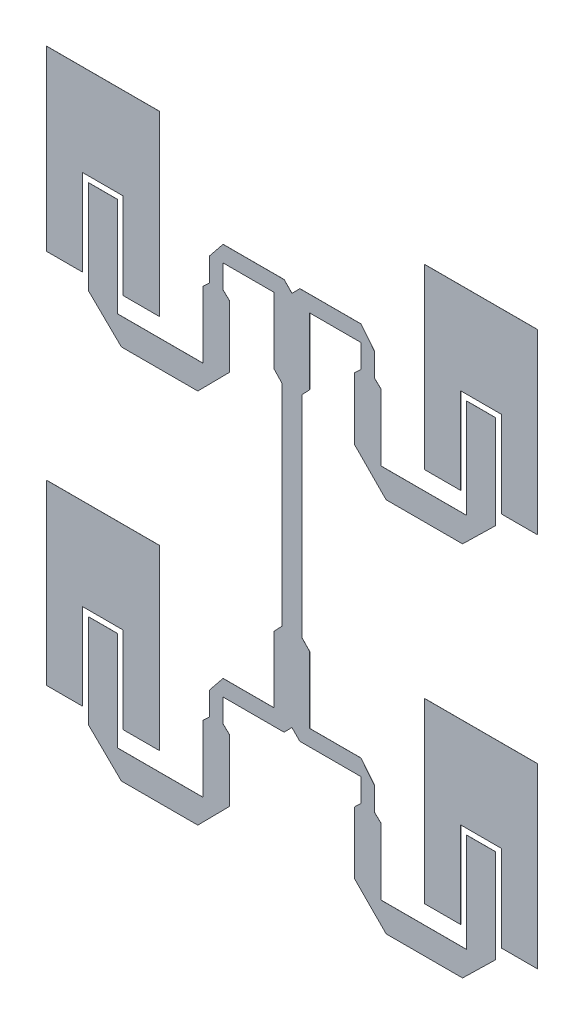
SolidWorks part; units mm, degrees
material "Медь"
ref_plane "Спереди" through (0, 0, 0) normal (0, 0, 1) x (1, 0, 0)
ref_plane "Сверху" through (0, 0, 0) normal (0, 1, 0) x (1, 0, 0)
ref_plane "Справа" through (0, 0, 0) normal (1, 0, 0) x (0, 0, -1)
sketch "Patch1" plane through (0, 0, 0) normal (0, 0, 1) x (1, 0, 0)
  line L0 (0, 0) -> (0, 64.0927) construction
  line L1 (-56.8537, 64.0927) -> (-30.6917, 64.0927)
  line L2 (-56.8537, 64.0927) -> (-56.8537, 22.9447)
  line L3 (-56.8537, 22.9447) -> (-48.4717, 22.9447)
  line L4 (-30.6917, 64.0927) -> (-30.6917, 22.9447)
  line L5 (-56.8537, 64.0927) -> (-30.6917, 22.9447) construction
  line L6 (-56.8537, 22.9447) -> (-30.6917, 64.0927) construction
  line L7 (-43.7727, 43.5187) -> (-43.7727, 22.9447) construction
  line L8 (43.7727, 43.5187) -> (43.7727, 22.9447) construction
  line L9 (-48.4717, 22.9447) -> (-48.4717, 42.926)
  line L10 (-48.4717, 42.926) -> (-39.0737, 42.926)
  line L11 (-39.0737, 22.9447) -> (-39.0737, 42.926)
  line L12 (-39.0737, 22.9447) -> (-30.6917, 22.9447)
  line L13 (56.8537, 22.9447) -> (30.6917, 64.0927) construction
  line L14 (56.8537, 64.0927) -> (30.6917, 22.9447) construction
  line L15 (39.0737, 22.9447) -> (30.6917, 22.9447)
  line L16 (39.0737, 22.9447) -> (39.0737, 42.926)
  line L17 (48.4717, 42.926) -> (39.0737, 42.926)
  line L18 (48.4717, 22.9447) -> (48.4717, 42.926)
  line L19 (30.6917, 64.0927) -> (30.6917, 22.9447)
  line L20 (56.8537, 22.9447) -> (48.4717, 22.9447)
  line L21 (56.8537, 64.0927) -> (56.8537, 22.9447)
  line L22 (56.8537, 64.0927) -> (30.6917, 64.0927)
  line L23 (-39.0737, -64.0927) -> (-30.6917, -64.0927)
  line L24 (-30.6917, -22.9447) -> (-30.6917, -64.0927)
  line L25 (-56.8537, -22.9447) -> (-30.6917, -22.9447)
  line L26 (-56.8537, -22.9447) -> (-30.6917, -64.0927) construction
  line L27 (-48.4717, -44.1113) -> (-39.0737, -44.1113)
  line L28 (-56.8537, -22.9447) -> (-56.8537, -64.0927)
  line L29 (-48.4717, -64.0927) -> (-48.4717, -44.1113)
  line L30 (-56.8537, -64.0927) -> (-30.6917, -22.9447) construction
  line L31 (-39.0737, -64.0927) -> (-39.0737, -44.1113)
  line L32 (-56.8537, -64.0927) -> (-48.4717, -64.0927)
  line L33 (-43.7727, -43.5187) -> (-43.7727, -64.0927) construction
  line L34 (43.7727, -43.5187) -> (43.7727, -64.0927) construction
  line L35 (56.8537, -64.0927) -> (30.6917, -22.9447) construction
  line L36 (56.8537, -22.9447) -> (30.6917, -64.0927) construction
  line L37 (56.8537, -64.0927) -> (48.4717, -64.0927)
  line L38 (39.0737, -64.0927) -> (39.0737, -44.1113)
  line L39 (48.4717, -64.0927) -> (48.4717, -44.1113)
  line L40 (56.8537, -22.9447) -> (56.8537, -64.0927)
  line L41 (48.4717, -44.1113) -> (39.0737, -44.1113)
  line L42 (56.8537, -22.9447) -> (30.6917, -22.9447)
  line L43 (30.6917, -22.9447) -> (30.6917, -64.0927)
  line L44 (39.0737, -64.0927) -> (30.6917, -64.0927)
  point P0 (-43.7727, 43.5187)
  point P24 (-43.7727, -43.5187)
  dimension "D1" = 41.148
  dimension "D2" = 26.162
  dimension "D3" = 43.7727
  dimension "D5" = 19.9813
  dimension "D6" = 8.382
  dimension "D4" = 43.5187
  dimension "D7" = 41.148
  dimension "D8" = 26.162
  dimension "D9" = 19.9813
  dimension "D10" = 8.382
  dimension "D11" = 43.7727
  dimension "D12" = 43.5187
sketch "Feed1" plane through (0, 0, 0) normal (0, 0, 1) x (1, 0, 0)
  line L0 (-48.4717, 42.926) -> (-39.0737, 42.926) construction
  line L1 (-47.117, 41.5713) -> (-40.4283, 41.5713)
  line L2 (-47.117, 41.5713) -> (-47.117, 19.8967)
  line L3 (-47.117, 19.8967) -> (-39.497, 12.446)
  line L4 (-40.4283, 41.5713) -> (-40.4283, 18.6267)
  line L5 (-48.4717, 22.9447) -> (-48.4717, 42.926) construction
  line L6 (-14.4357, 19.8967) -> (-21.8017, 12.446)
  line L7 (-20.6163, 34.036) -> (-19.0923, 35.4753)
  line L8 (14.4357, -67.1407) -> (14.4357, -52.832)
  line L9 (-39.497, 12.446) -> (-21.8017, 12.446)
  line L10 (-20.6163, 18.6267) -> (-20.6163, 34.036)
  line L11 (1.8203, 44.7887) -> (0, 42.926)
  line L12 (40.4283, -68.4107) -> (20.6163, -68.4107)
  line L13 (-19.0923, 40.894) -> (-19.0923, 35.4753)
  line L14 (39.497, -74.5913) -> (21.8017, -74.5913)
  line L15 (-40.4283, 18.6267) -> (-20.6163, 18.6267)
  line L16 (-14.4357, -67.1407) -> (-21.8017, -74.5913)
  line L17 (-19.0923, 40.894) -> (-15.9597, 44.7887)
  line L18 (-14.4357, 19.8967) -> (-14.4357, 34.2053)
  line L19 (-15.9597, 41.0633) -> (-4.1063, 41.0633)
  line L20 (-15.9597, 41.0633) -> (-15.9597, 35.6447)
  line L21 (-15.9597, 35.6447) -> (-14.4357, 34.2053)
  line L22 (0, 0) -> (0, 64.0927) construction
  line L23 (-15.9597, 44.7887) -> (-1.8203, 44.7887)
  line L24 (-20.6163, -53.0013) -> (-19.0923, -51.562)
  line L25 (-15.9597, -45.974) -> (-1.8203, -45.974)
  line L26 (-1.8203, 44.7887) -> (0, 42.926)
  line L27 (15.9597, 44.7887) -> (1.8203, 44.7887)
  line L28 (15.9597, 35.6447) -> (14.4357, 34.2053)
  line L29 (15.9597, 41.0633) -> (15.9597, 35.6447)
  line L30 (15.9597, 41.0633) -> (4.1063, 41.0633)
  line L31 (14.4357, 19.8967) -> (14.4357, 34.2053)
  line L32 (19.0923, 40.894) -> (15.9597, 44.7887)
  line L33 (-20.6163, -68.4107) -> (-20.6163, -53.0013)
  line L34 (40.4283, 18.6267) -> (20.6163, 18.6267)
  line L35 (-19.0923, -46.1433) -> (-15.9597, -42.2487)
  line L36 (19.0923, 40.894) -> (19.0923, 35.4753)
  line L37 (-47.117, -45.466) -> (-40.4283, -45.466)
  line L38 (20.6163, 18.6267) -> (20.6163, 34.036)
  line L39 (39.497, 12.446) -> (21.8017, 12.446)
  line L40 (20.6163, 34.036) -> (19.0923, 35.4753)
  line L41 (14.4357, 19.8967) -> (21.8017, 12.446)
  line L42 (40.4283, 41.5713) -> (40.4283, 18.6267)
  line L43 (47.117, 19.8967) -> (39.497, 12.446)
  line L44 (47.117, 41.5713) -> (47.117, 19.8967)
  line L45 (47.117, 41.5713) -> (40.4283, 41.5713)
  line L46 (-47.117, -67.1407) -> (-39.497, -74.5913)
  line L47 (19.0923, -46.1433) -> (19.0923, -51.562)
  line L48 (14.4357, -67.1407) -> (21.8017, -74.5913)
  line L49 (40.4283, -45.466) -> (40.4283, -68.4107)
  line L50 (47.117, -45.466) -> (47.117, -67.1407)
  line L51 (-4.1063, 25.654) -> (-4.1063, 41.0633)
  line L52 (15.9597, -51.3927) -> (14.4357, -52.832)
  line L53 (-40.4283, -45.466) -> (-40.4283, -68.4107)
  line L54 (15.9597, -42.2487) -> (4.1063, -42.2487)
  line L55 (15.9597, -45.974) -> (15.9597, -51.3927)
  line L56 (20.6163, -53.0013) -> (19.0923, -51.562)
  line L57 (47.117, -45.466) -> (40.4283, -45.466)
  line L58 (-47.117, -45.466) -> (-47.117, -67.1407)
  line L59 (-15.9597, -51.3927) -> (-14.4357, -52.832)
  line L60 (20.6163, -68.4107) -> (20.6163, -53.0013)
  line L61 (-40.4283, -68.4107) -> (-20.6163, -68.4107)
  line L62 (-15.9597, -42.2487) -> (-4.1063, -42.2487)
  line L63 (-39.497, -74.5913) -> (-21.8017, -74.5913)
  line L64 (-15.9597, -45.974) -> (-15.9597, -51.3927)
  line L65 (-14.4357, -67.1407) -> (-14.4357, -52.832)
  line L66 (15.9597, -45.974) -> (1.8203, -45.974)
  line L67 (0, -86.952) -> (0, -22.8593) construction
  line L68 (47.117, -67.1407) -> (39.497, -74.5913)
  line L69 (4.1063, 25.654) -> (4.1063, 41.0633)
  line L70 (-19.0923, -46.1433) -> (-19.0923, -51.562)
  line L71 (19.0923, -46.1433) -> (15.9597, -42.2487)
  line L72 (-1.8203, -45.974) -> (0, -44.1113)
  line L73 (1.8203, -45.974) -> (0, -44.1113)
  line L74 (-4.1063, -42.2487) -> (-4.1063, -26.8393)
  line L75 (4.1063, -42.2487) -> (4.103, -26.8393)
  line L76 (-2.33, 23.7913) -> (-4.1063, 25.654)
  line L77 (-48.4717, -44.1113) -> (-39.0737, -44.1113) construction
  line L78 (-39.0737, -64.0927) -> (-39.0737, -44.1113) construction
  line L79 (-4.1063, -26.8393) -> (-2.33, -24.9767)
  line L80 (4.103, -26.8393) -> (2.3267, -24.9767)
  line L81 (-2.33, -24.9767) -> (-2.33, 23.7913)
  line L82 (2.3267, -24.9767) -> (2.3267, 23.7913)
  line L83 (2.3267, 23.7913) -> (4.1063, 25.654)
  dimension "D1" = 1.3547
  dimension "D2" = 1.3547
  dimension "D5" = 7.4507
  dimension "D6" = 7.62
  dimension "D7" = 21.6747
  dimension "D8" = 17.6953
  dimension "D11" = 7.366
  dimension "D13" = 14.3087
  dimension "D14" = 3.1327
  dimension "D16" = 1.4393
  dimension "D17" = 1.524
  dimension "D15" = 5.4187
  dimension "D18" = 1.4393
  dimension "D19" = 7.4507
  dimension "D23" = 5.4187
  dimension "D21" = 3.1327
  dimension "D22" = 3.7253
  dimension "D25" = 1.8627
  dimension "D24" = 14.1393
  dimension "D20" = 1.8203
  dimension "D10" = 15.4093
  dimension "D12" = 6.1807
  dimension "D9" = 6.1807
  dimension "D3" = 1.3547
  dimension "D4" = 7.4507
  dimension "D27" = 7.62
  dimension "D28" = 21.6747
  dimension "D29" = 17.6953
  dimension "D30" = 7.366
  dimension "D31" = 14.3087
  dimension "D32" = 3.1327
  dimension "D33" = 1.4393
  dimension "D34" = 1.524
  dimension "D35" = 5.4187
  dimension "D36" = 1.4393
  dimension "D37" = 7.4507
  dimension "D38" = 5.4187
  dimension "D39" = 3.1327
  dimension "D40" = 3.7253
  dimension "D45" = 15.4093
  dimension "D46" = 6.1807
  dimension "D47" = 6.1807
  dimension "D41" = 1.8627
  dimension "D42" = 4.1063
  dimension "D43" = 4.1063
  dimension "D44" = 1.3547
  dimension "D48" = 1.3547
  dimension "D49" = 1.3547
  dimension "D50" = 1.3547
  dimension "D51" = 15.4093
  dimension "D52" = 4.6567
  dimension "D53" = 1.8627
  dimension "D54" = 1.8627
  dimension "D56" = 4.1063
  dimension "D26" = 15.4093
  dimension "D55" = 8.2127
  dimension "D57" = 15.4093
  dimension "D58" = 8.2127
  dimension "D59" = 1.8627
  dimension "D60" = 1.8627
  dimension "D61" = 4.6567
extrude "Feed" add sketch "Feed1" along normal blind 0.018
extrude "Patch" add sketch "Patch1" along normal blind 0.018 separate body
equation "\"dpi\"= 25.4 / 300"
equation "\"D2@Patch1\" = \"patch_w\""
equation "\"D1@Patch1\" = \"patch_h\""
equation "\"D3@Patch1\" = \"patch_pos_hor\""
equation "\"D6@Patch1\" = \"patch_border_w\""
equation "\"D5@Patch1\" = \"patch_border_h\""
equation "\"D4@Patch1\" = \"patch_pos_vert\""
equation "\"patch_w\"= 309 * \"dpi\""
equation "\"patch_h\"= 486 * \"dpi\""
equation "\"patch_border_w\"= 99 * \"dpi\""
equation "\"patch_pos_hor\"= 517 * \"dpi\""
equation "\"patch_border_h\"= 236 * \"dpi\""
equation "\"patch_pos_vert\"= 514 * \"dpi\""
equation "\"D10@Patch1\" = \"patch_border_w\""
equation "\"D8@Patch1\" = \"patch_w\""
equation "\"D11@Patch1\" = \"patch_pos_hor\""
equation "\"D12@Patch1\" = \"patch_pos_vert\""
equation "\"D7@Patch1\" = \"patch_h\""
equation "\"D9@Patch1\" = \"patch_border_h\""
equation "\"mstrp_border\"= 16 * \"dpi\""
equation "\"D1@Feed1\"=\"mstrp_border\""
equation "\"D2@Feed1\"=\"mstrp_border\""
equation "\"D3@Feed1\"=\"mstrp_border\""
equation "\"mstrp_1h\"= 256 * \"dpi\""
equation "\"D5@Feed1\"=88*\"dpi\""
equation "\"D6@Feed1\"=90*\"dpi\""
equation "\"D7@Feed1\"=\"mstrp_1h\""
equation "\"mstrp_2h\"= 73 * \"dpi\""
equation "\"mstrp_2w\"= 209 * \"dpi\""
equation "\"D8@Feed1\"=\"mstrp_2w\""
equation "\"D9@Feed1\"=\"mstrp_2h\""
equation "\"D10@Feed1\"=182*\"dpi\""
equation "\"D11@Feed1\"=87*\"dpi\""
equation "\"D12@Feed1\"=73*\"dpi\""
equation "\"D13@Feed1\"=169*\"dpi\""
equation "\"D14@Feed1\"=37*\"dpi\""
equation "\"D15@Feed1\"=64*\"dpi\""
equation "\"D16@Feed1\"=17*\"dpi\""
equation "\"D17@Feed1\"=18*\"dpi\""
equation "\"D18@Feed1\"=17*\"dpi\""
equation "\"D19@Feed1\"=88*\"dpi\""
equation "\"D20@Feed1\"=21.5*\"dpi\""
equation "\"D21@Feed1\"=37*\"dpi\""
equation "\"D22@Feed1\"=44*\"dpi\""
equation "\"D24@Feed1\"=167*\"dpi\""
equation "\"D25@Feed1\"=22*\"dpi\""
equation "\"D26@Feed1\"=182*\"dpi\""
equation "\"D23@Feed1\"=64*\"dpi\""
equation "\"D41@Feed1\"=22*\"dpi\""
equation "\"D42@Feed1\"=(97/2)*\"dpi\""
equation "\"D43@Feed1\"=97/2*\"dpi\""
equation "\"D44@Feed1\"=\"mstrp_border\""
equation "\"D48@Feed1\"=\"mstrp_border\""
equation "\"D49@Feed1\"=\"mstrp_border\""
equation "\"D50@Feed1\"=\"mstrp_border\""
equation "\"D51@Feed1\"=182*\"dpi\""
equation "\"D53@Feed1\"=22*\"dpi\""
equation "\"D54@Feed1\"=22*\"dpi\""
equation "\"D52@Feed1\"=55*\"dpi\""
equation "\"D55@Feed1\"=97*\"dpi\""
equation "\"D56@Feed1\"=97/2*\"dpi\""
equation "\"D57@Feed1\"=182*\"dpi\""
equation "\"D58@Feed1\"=97*\"dpi\""
equation "\"D59@Feed1\"=22*\"dpi\""
equation "\"D60@Feed1\"=22*\"dpi\""
equation "\"D61@Feed1\"=55*\"dpi\""
